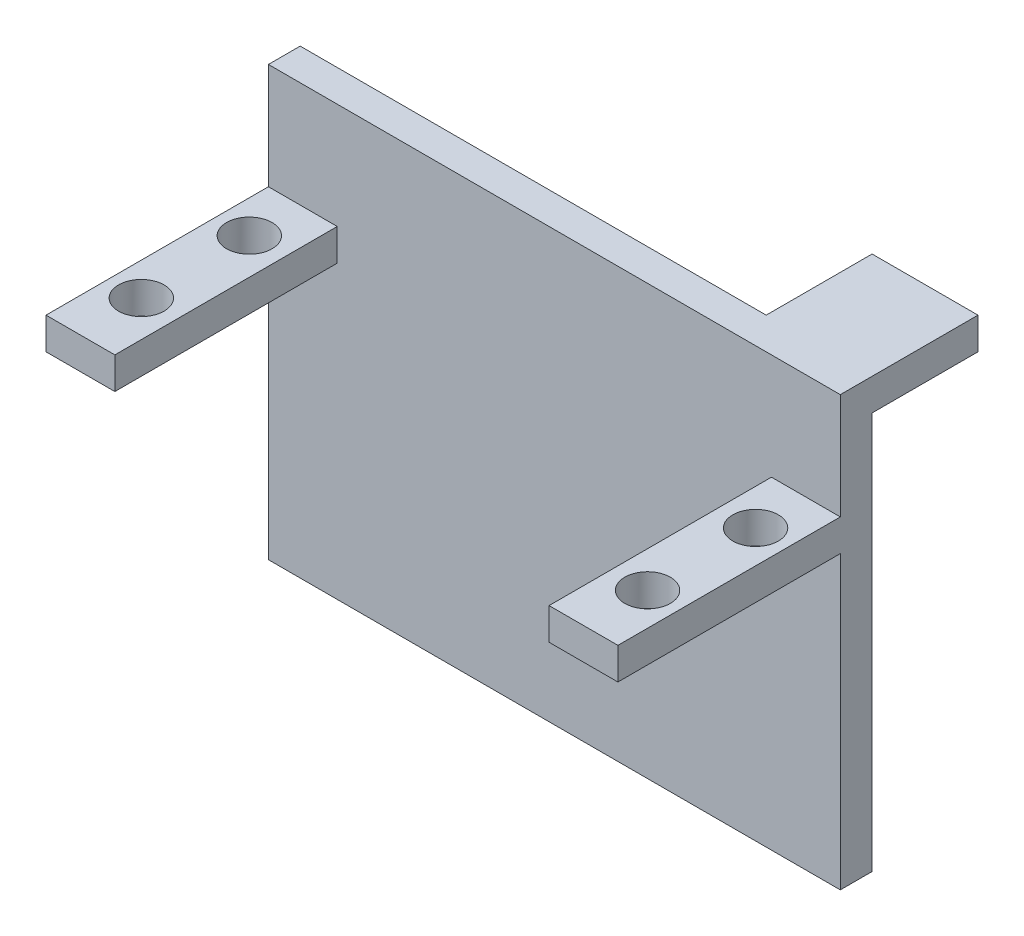
SolidWorks part; units mm, degrees
ref_plane "Front Plane" through (0, 0, 0) normal (0, 0, 1) x (1, 0, 0)
ref_plane "Top Plane" through (0, 0, 0) normal (0, 1, 0) x (1, 0, 0)
ref_plane "Right Plane" through (0, 0, 0) normal (1, 0, 0) x (0, 0, -1)
sketch "Sketch1" plane through (0, 0, 0) normal (0, 0, 1) x (1, 0, 0)
  line L0 (33.9411, 9.3925) -> (33.9411, 6.8925) construction
  line L1 (-19.5589, 16.8925) -> (34.4411, 16.8925)
  line L2 (-19.5589, 16.8925) -> (-19.5589, -23.6075)
  line L3 (-19.5589, -23.6075) -> (34.4411, -23.6075)
  line L4 (34.4411, 16.8925) -> (34.4411, -23.6075)
  line L5 (-19.0589, 9.3925) -> (-19.0589, 6.8925) construction
  line L6 (23.1911, -19.6075) -> (-8.3089, -19.6075) construction
  dimension "D1" = 0.5
  dimension "D2" = 0.5
  dimension "D3" = 40.5
  dimension "D4" = 4
extrude "Boss-Extrude1" add sketch "Sketch1" along normal blind 3
sketch "Sketch3" plane through (0, 0, 3) normal (0, 0, 1) x (1, 0, 0)
  line L0 (34.4411, -23.6075) -> (34.4411, 16.8925) construction
  line L1 (34.4411, 3.8925) -> (34.4411, 6.8925)
  line L2 (34.4411, 6.8925) -> (27.9411, 6.8925)
  line L3 (27.9411, 6.8925) -> (27.9411, 3.8925)
  line L4 (27.9411, 3.8925) -> (34.4411, 3.8925)
  line L5 (27.4411, 6.8925) -> (27.4411, -18.1075) construction
  line L6 (26.764, 6.8925) -> (32.1295, 6.8925) construction
  line L7 (7.4411, 16.8925) -> (7.4411, -23.6075) construction
  line L8 (34.4411, 16.8925) -> (-19.5589, 16.8925) construction
  line L9 (-19.5589, -23.6075) -> (34.4411, -23.6075) construction
  line L10 (-19.5589, 3.8925) -> (-19.5589, 6.8925)
  line L11 (-13.0589, 3.8925) -> (-19.5589, 3.8925)
  line L12 (-13.0589, 6.8925) -> (-13.0589, 3.8925)
  line L13 (-19.5589, 6.8925) -> (-13.0589, 6.8925)
  dimension "D1" = 3
  dimension "D2" = 0.5
extrude "Boss-Extrude2" add sketch "Sketch3" along normal blind 21
sketch "Sketch4" plane through (0, 0, 0) normal (0, 0, -1) x (-1, 0, 0)
  line L1 (-24.4411, 16.8925) -> (-24.4411, 13.8925)
  line L2 (-34.4411, -23.6075) -> (-34.4411, 16.8925) construction
  line L3 (-34.4411, 16.8925) -> (19.5589, 16.8925) construction
  line L9 (-24.4411, 16.8925) -> (-34.4411, 16.8925)
  line L13 (-34.4411, 16.8925) -> (-34.4411, 13.8925)
  line L14 (-34.4411, 13.8925) -> (-24.4411, 13.8925)
  line M8 (19.5589, 16.8925) -> (-34.4411, 16.8925)
  dimension "D2" = 10
  dimension "D1" = 3
extrude "Boss-Extrude3" add sketch "Sketch4" along normal blind 10 contours L13 L14 L1 M8
sketch "Sketch5" plane through (0, 6.8925, 0) normal (0, 1, 0) x (1, 0, 0)
  circle A0 centre (31.3411, -18.1) radius 2.15
  circle A1 centre (31.3411, -7.9) radius 2.15
  circle A2 centre (-16.4589, -18.1) radius 2.15
  circle A3 centre (-16.4589, -7.9) radius 2.15
extrude "Cut-Extrude1" cut sketch "Sketch5" against normal up to surface (3 mm away) up to face at (-16.3089, 3.8925, 13.5)
